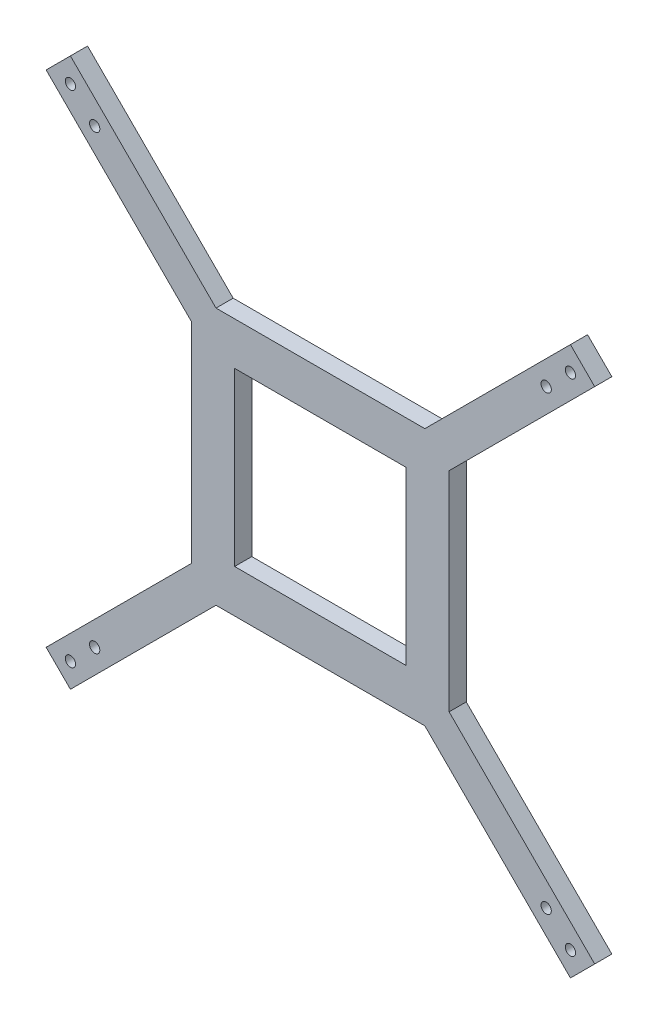
SolidWorks part; units mm, degrees
ref_plane "Front Plane" through (0, 0, 0) normal (0, 0, 1) x (1, 0, 0)
ref_plane "Top Plane" through (0, 0, 0) normal (0, 1, 0) x (1, 0, 0)
ref_plane "Right Plane" through (0, 0, 0) normal (1, 0, 0) x (0, 0, -1)
sketch "Sketch1" plane through (0, 0, 0) normal (0, 0, 1) x (1, 0, 0)
  line L0 (-79.9264, -72.8553) -> (-37.5, -30.4289)
  line L14 (-30.4289, 37.5) -> (30.4289, 37.5)
  line L19 (-37.5, 30.4289) -> (-37.5, -30.4289)
  line L20 (-30.4289, -37.5) -> (30.4289, -37.5)
  line L62 (37.5, 30.4289) -> (37.5, -30.4289)
  line L63 (-37.5, 37.5) -> (37.5, -37.5) construction
  line L67 (-25, -25) -> (37.5, 37.5) construction
  line L73 (-25, 25) -> (25, 25)
  line L74 (-25, 25) -> (-25, -25)
  line L75 (-25, -25) -> (25, -25)
  line L76 (25, 25) -> (25, -25)
  line L77 (-25, 25) -> (25, -25) construction
  line L78 (-25, -25) -> (25, 25) construction
  line L79 (-79.9264, -72.8553) -> (-72.8553, -79.9264)
  line L81 (-72.8553, -79.9264) -> (-30.4289, -37.5)
  line L82 (-76.3909, -76.3909) -> (-25, -25) construction
  line L83 (0, 62.8023) -> (0, -62.1182) construction
  line L84 (0, 0) -> (-94.0187, 0) construction
  line L85 (-94.0187, 0) -> (102.0335, 0) construction
  line L86 (79.9264, -72.8553) -> (72.8553, -79.9264)
  line L87 (72.8553, -79.9264) -> (30.4289, -37.5)
  line L88 (79.9264, -72.8553) -> (37.5, -30.4289)
  line L89 (79.9264, 72.8553) -> (72.8553, 79.9264)
  line L90 (72.8553, 79.9264) -> (30.4289, 37.5)
  line L91 (79.9264, 72.8553) -> (37.5, 30.4289)
  line L92 (-79.9264, 72.8553) -> (-72.8553, 79.9264)
  line L93 (-72.8553, 79.9264) -> (-30.4289, 37.5)
  line L94 (-79.9264, 72.8553) -> (-37.5, 30.4289)
  line L95 (76.3909, 76.3909) -> (-76.3909, -76.3909) construction
  circle A0 centre (72.8553, 72.8553) radius 1.5
  circle A1 centre (65.7843, 65.7843) radius 1.5
  circle A2 centre (-65.7843, 65.7843) radius 1.5
  circle A3 centre (-72.8553, 72.8553) radius 1.5
  circle A4 centre (72.8553, -72.8553) radius 1.5
  circle A5 centre (65.7843, -65.7843) radius 1.5
  circle A6 centre (-72.8553, -72.8553) radius 1.5
  circle A7 centre (-65.7843, -65.7843) radius 1.5
  point P0 (0, 0)
  point P6 (0, 0)
  dimension "D6" = 12.5
  dimension "D7" = 12.5
  dimension "D32" = 3
  dimension "D33" = 3
  dimension "D1" = 75
  dimension "D2" = 75
  dimension "D3" = 50
  dimension "D4" = 50
  dimension "D5" = 12.5
  dimension "D8" = 12.5
  dimension "D9" = 5
  dimension "D10" = 94.0187
  dimension "D11" = 10
  dimension "D12" = 60
  dimension "D16" = 10
  dimension "D17" = 10
  dimension "D22" = 10
  dimension "D23" = 60.8579
  dimension "D24" = 60.8579
  dimension "D25" = 60.8579
  dimension "D26" = 60.8579
  dimension "D27" = 50
  dimension "D28" = 50
  dimension "D29" = 50
  dimension "D30" = 50
  dimension "D31" = 60.8579
  dimension "D34" = 10
  dimension "D35" = 5
extrude "Boss-Extrude1" add sketch "Sketch1" along normal blind 5
